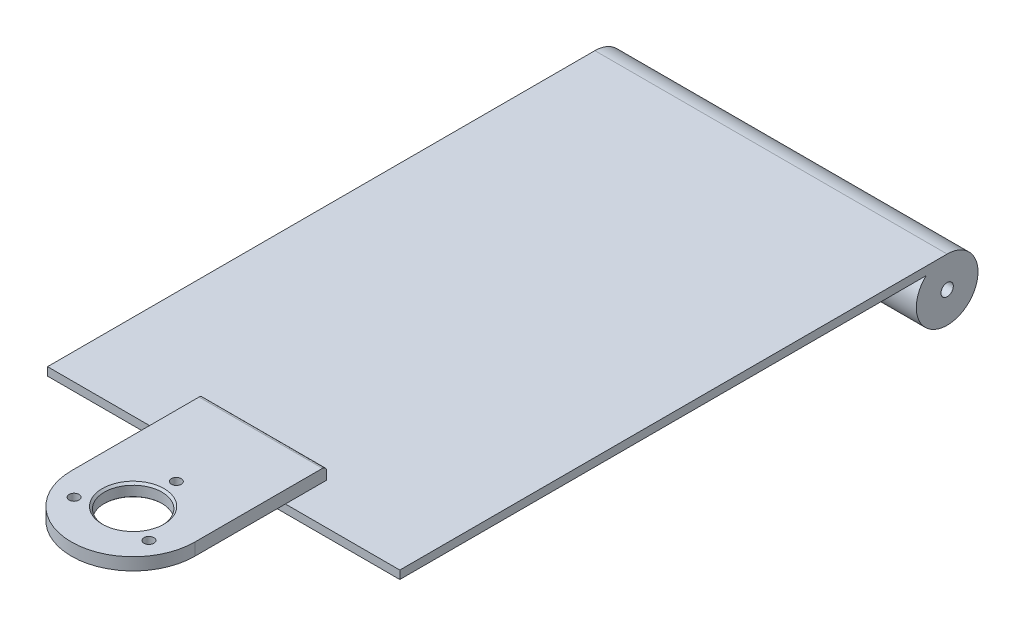
SolidWorks part; units mm, degrees
ref_plane "前视基准面" through (0, 0, 0) normal (0, 0, 1) x (1, 0, 0)
ref_plane "上视基准面" through (0, 0, 0) normal (0, 1, 0) x (1, 0, 0)
ref_plane "右视基准面" through (0, 0, 0) normal (1, 0, 0) x (0, 0, -1)
sketch "Sketch1" plane through (0, 0, 0) normal (1, 0, 0) x (0, 0, -1)
  line L0 (0, 7.5) -> (-133, 7.5)
  line L1 (-133, 7.5) -> (-133, 5.5)
  line L2 (-133, 5.5) -> (-5.099, 5.5)
  arc A0 (-5.099, 5.5) -> (0, 7.5) centre (0, 0) ccw
  circle A1 centre (0, 0) radius 1.5
  dimension "D1" = 2
  dimension "D2" = 15
  dimension "D3" = 133
extrude "Boss-Extrude1" add sketch "Sketch1" along normal mid plane 85.6
sketch "Sketch2" plane through (0, 7.5, 0) normal (0, 1, 0) x (1, 0, 0)
  line L0 (0, -133) -> (0, -140) construction
  line L1 (42.8, -133) -> (-42.8, -133) construction
  line L2 (15, -155) -> (15, -133)
  line L3 (15, -133) -> (-15, -133)
  line L4 (-15, -133) -> (-15, -155)
  arc A0 (-15, -155) -> (15, -155) centre (0, -155) ccw
  dimension "D1" = 22
extrude "Boss-Extrude2" add sketch "Sketch2" along normal blind 3 separate body
sketch "Sketch3" plane through (15, 0, 0) normal (1, 0, 0) x (0, 0, -1)
  line L0 (-133, 10.5) -> (-133, 7.5)
  line L1 (-133, 7.5) -> (-123, 7.5)
  line L2 (0, 7.5) -> (-133, 7.5) construction
  line L3 (-133, 10.5) -> (-124, 10.5)
  line L4 (-123, 9.5) -> (-123, 7.5)
  arc A0 (-124, 10.5) -> (-123, 9.5) centre (-124, 9.5) cw
  dimension "D2" = 1
  dimension "D1" = 10
extrude "Boss-Extrude3" add sketch "Sketch3" against normal up to surface (30 mm away) up to face at (-15, 9, 144)
sketch "Sketch4" plane through (0, 10.5, 0) normal (0, 1, 0) x (1, 0, 0)
  circle A0 centre (0, -155) radius 7
extrude "Cut-Extrude1" cut sketch "Sketch4" against normal up to next
sketch "Sketch5" plane through (0, 10.5, 0) normal (0, 1, 0) x (1, 0, 0)
  circle A0 centre (0, -155) radius 10.5 construction
  circle A1 centre (0, -144.5) radius 1.2
  circle A2 centre (9.0933, -160.25) radius 1.2
  circle A3 centre (-9.0933, -160.25) radius 1.2
  dimension "D1" = 3
extrude "Cut-Extrude2" cut sketch "Sketch5" against normal blind 0.1
sketch "Sketch6" plane through (0, 0, 0) normal (1, 0, 0) x (0, 0, -1)
  line L0 (-144.5, 7.5) -> (-142, 7.5)
  line L1 (-144.5, 10.5) -> (-144.5, 7.5) construction
  line L2 (-155, 7.5) -> (-133, 7.5) construction
  line L4 (-143.3, 9.8) -> (-143.3, 10.5)
  line L5 (-143.3, 10.5) -> (-145.7, 10.5) construction
  line L6 (-143.3, 10.5) -> (-144.5, 10.5)
  line L7 (-144.5, 10.5) -> (-144.5, 7.5)
  line L8 (-142, 7.5) -> (-143.3, 8.8)
  line L9 (-143.3, 8.8) -> (-143.3, 9.8)
  dimension "D1" = 2.5
revolve "Cut-Revolve1" cut sketch "Sketch6" angle 360 about L1
ref_axis "Axis1" through (0, 7.5, 155) along (0, 1, 0)
pattern_circular "CirPattern1" count 3 every 120 about axis through (0, 0, 155) along (0, 1, 0) of "Cut-Revolve1"
sketch "Sketch7" plane through (0, 0, 0) normal (1, 0, 0) x (0, 0, -1)
  line L1 (-148, 7.5) -> (-147.9, 7.5)
  line L2 (-148, 10.5) -> (-148, 10.4612) construction
  line L3 (-155, 7.5) -> (-133, 7.5) construction
  line L4 (-148, 10.5) -> (-147.5, 10.5)
  line L5 (-144.5, 10.5) -> (-165.5, 10.5) construction
  line L6 (-147.5, 10.5) -> (-148, 10)
  line L8 (-147.9, 7.5) -> (-148, 7.6)
  line L9 (-148, 7.6) -> (-148, 7.5)
  line L10 (-148, 10.5) -> (-155, 10.5)
  line L11 (-155, 10.5) -> (-155, 10)
  line L12 (-155, 7.5) -> (-155, 10.5) construction
  line L13 (-155, 10) -> (-148, 10)
  line L14 (-148, 10) -> (-148, 7.5) construction
  dimension "D1" = 0.1
revolve "Cut-Revolve2" cut sketch "Sketch7" angle 360 about axis through (0, 7.5, 155) along (0, 1, 0)
